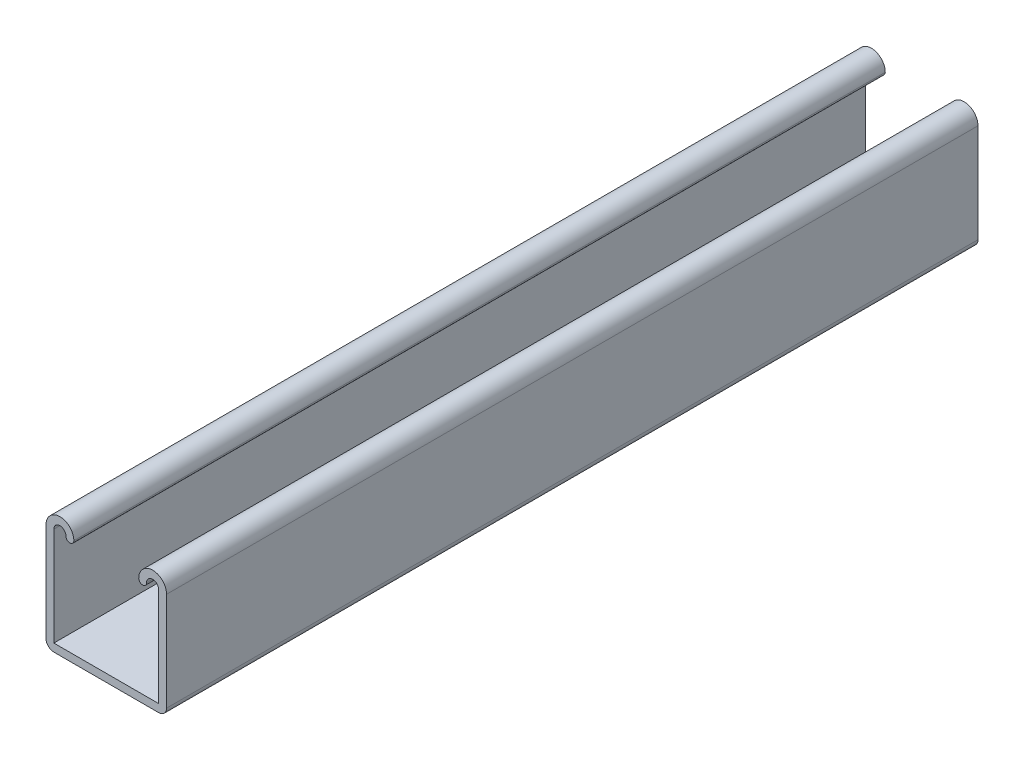
SolidWorks part; units mm, degrees
ref_plane "Front Plane" through (0, 0, 0) normal (0, 0, 1) x (1, 0, 0)
ref_plane "Top Plane" through (0, 0, 0) normal (0, 1, 0) x (1, 0, 0)
ref_plane "Right Plane" through (0, 0, 0) normal (1, 0, 0) x (0, 0, -1)
sketch "Sketch1" plane through (0, 0, 0) normal (0, 0, 1) x (1, 0, 0)
  line L0 (0, 0) -> (35.98, 0)
  line L1 (17.99, 2.6924) -> (17.99, -3.3917) construction
  line L2 (35.98, 2.6924) -> (0, 2.6924)
  line L3 (35.98, 19.6088) -> (0, 19.6088) construction
  line L4 (35.98, 2.6924) -> (35.98, 36.5252)
  line L5 (38.6724, 2.6924) -> (38.6724, 36.5252)
  line L6 (-2.6924, 2.6924) -> (-2.6924, 36.5252)
  line L7 (0, 2.6924) -> (0, 36.5252)
  line L8 (17.99, 19.6088) -> (17.99, 2.6924) construction
  arc A0 (35.98, 0) -> (38.6724, 2.6924) centre (35.98, 2.6924) ccw
  arc A1 (35.98, 36.5252) -> (31.8144, 36.5252) centre (33.8972, 36.5252) ccw
  arc A2 (38.6724, 36.5252) -> (29.122, 36.5252) centre (33.8972, 36.5252) ccw
  arc A3 (29.122, 36.5252) -> (31.8144, 36.5252) centre (30.4682, 36.5252) ccw
  arc A4 (6.858, 36.5252) -> (4.1656, 36.5252) centre (5.5118, 36.5252) cw
  arc A5 (-2.6924, 36.5252) -> (6.858, 36.5252) centre (2.0828, 36.5252) cw
  arc A6 (0, 36.5252) -> (4.1656, 36.5252) centre (2.0828, 36.5252) cw
  arc A7 (0, 0) -> (-2.6924, 2.6924) centre (0, 2.6924) cw
  point P25 (17.99, 19.6088)
extrude "Boss-Extrude1" add sketch "Sketch1" along normal blind 278.384
ref_plane "Plane1" through (0, 0, 0) normal (0, -1, 0) x (-1, 0, 0)
sketch "Sketch2" plane through (0, 0, 0) normal (0, -1, 0) x (-1, 0, 0)
  line L0 (-17.99, 0) -> (-17.99, -42.164) construction
  line L1 (0, 0) -> (-35.98, 0) construction
  circle A0 centre (-17.99, -42.164) radius 7.112
extrude "Cut-Extrude1" cut sketch "Sketch2" against normal through all
pattern_linear "LPattern1" count 5 spacing 47.752 along (0, 0, 1) of "Cut-Extrude1"
